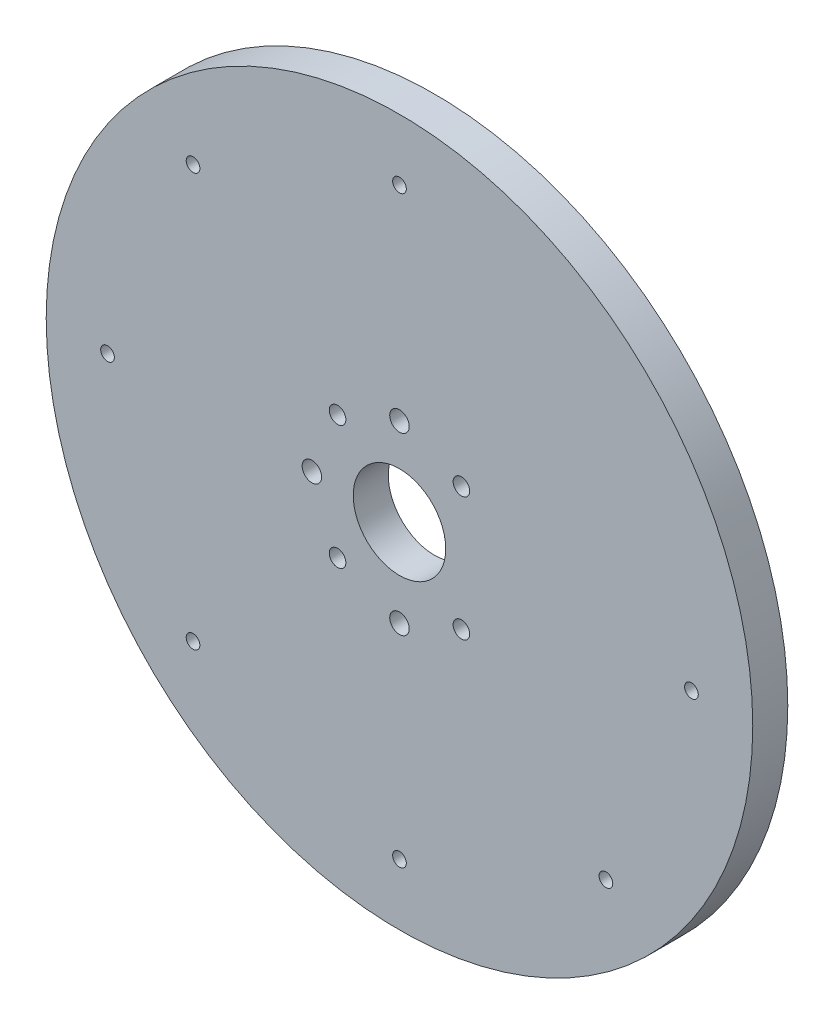
SolidWorks part; units mm, degrees
material "Balsa"
ref_plane "Front Plane" through (0, 0, 0) normal (0, 0, 1) x (1, 0, 0)
ref_plane "Top Plane" through (0, 0, 0) normal (0, 1, 0) x (1, 0, 0)
ref_plane "Right Plane" through (0, 0, 0) normal (1, 0, 0) x (0, 0, -1)
sketch "Sketch1" plane through (0, 0, 0) normal (0, 0, 1) x (1, 0, 0)
  circle A0 centre (35.3553, -35.3553) radius 1.25
  circle A2 centre (0, 0) radius 60.5
  circle A3 centre (0, 0) radius 8
  circle A4 centre (0, 0) radius 15 construction
  circle A6 centre (0, 0) radius 50 construction
  circle A27 centre (0, -15) radius 1.75
  circle A28 centre (10.6066, -10.6066) radius 1.5
  circle A30 centre (0, -50) radius 1.25
  circle A31 centre (-15, 0) radius 1.75
  circle A32 centre (-10.6066, -10.6066) radius 1.5
  circle A33 centre (0, 15) radius 1.75
  circle A34 centre (-10.6066, 10.6066) radius 1.5
  circle A35 centre (15, 0) radius 1.75 construction
  circle A36 centre (10.6066, 10.6066) radius 1.5
  circle A38 centre (-35.3553, -35.3553) radius 1.25
  circle A40 centre (-50, 0) radius 1.25
  circle A42 centre (-35.3553, 35.3553) radius 1.25
  circle A44 centre (0, 50) radius 1.25
  circle A46 centre (35.3553, 35.3553) radius 1.25 construction
  circle A48 centre (50, 0) radius 1.25
  circle A63 centre (35.3553, -35.3553) radius 1.25 [skipped]
  dimension "D1" = 121
  dimension "D4" = 45
  dimension "D6" = 100
  dimension "D8" = 30
  dimension "D15" = 2.5
  dimension "D17" = 3.5
  dimension "D18" = 3
  dimension "D22" = 16
  dimension "D23" = 2.5
  dimension "D3" = 45
  dimension "D5" = 45
  dimension "D20" = 4
  dimension "D24" = 4
extrude "Boss-Extrude1" add sketch "Sketch1" along normal blind 6
other "Move Face1" face at (36.6053, -35.3553, 6) face at (8, 0, 6) face at (1.75, -15, 6) face at (12.1066, -10.6066, 6) face at (1.25, -50, 6) face at (-34.1053, -35.3553, 6) face at (-13.25, 0, 6) face at (-9.1066, -10.6066, 6) face at (1.75, 15, 6) face at (-9.1066, 10.6066, 6) face at (12.1066, 10.6066, 6) face at (-48.75, 0, 6) face at (-34.1053, 35.3553, 6) face at (1.25, 50, 6) face at (51.25, 0, 6) parameters "D1"=0.08
